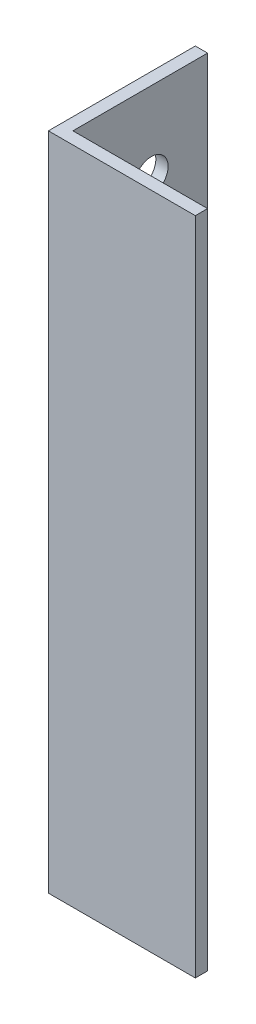
SolidWorks part; units mm, degrees
material "1060 Alloy"
ref_plane "Front Plane" through (0, 0, 0) normal (0, 0, 1) x (1, 0, 0)
ref_plane "Top Plane" through (0, 0, 0) normal (0, 1, 0) x (1, 0, 0)
ref_plane "Right Plane" through (0, 0, 0) normal (1, 0, 0) x (0, 0, -1)
sketch "Sketch1" plane through (0, 0, 0) normal (0, 1, 0) x (1, 0, 0)
  line L0 (0, 0) -> (0, 19.05)
  line L1 (0, 0) -> (19.05, 0)
  line L2 (19.05, 0) -> (19.05, 1.5875)
  line L3 (19.05, 1.5875) -> (1.5875, 1.5875)
  line L4 (1.5875, 1.5875) -> (1.5875, 19.05)
  line L5 (1.5875, 19.05) -> (0, 19.05)
  dimension "D1" = 19.05
  dimension "D2" = 1.5875
extrude "Boss-Extrude1" add sketch "Sketch1" along normal blind 85.598
sketch "Sketch2" plane through (0, 0, 0) normal (-1, 0, 0) x (0, 0, 1)
  line L0 (-19.05, 85.598) -> (0, 85.598) construction
  line L4 (-19.05, 0) -> (0, 0) construction
  line L5 (-1.5875, 85.598) -> (-1.5875, 0) construction
  circle A0 centre (-11.7475, 75.438) radius 2.1828
  circle A1 centre (-11.7475, 10.16) radius 2.1828
  dimension "D1" = 10.16
  dimension "D2" = 10.16
  dimension "D3" = 10.16
  dimension "D5" = 4.3656
extrude "Cut-Extrude1" cut sketch "Sketch2" against normal through all
